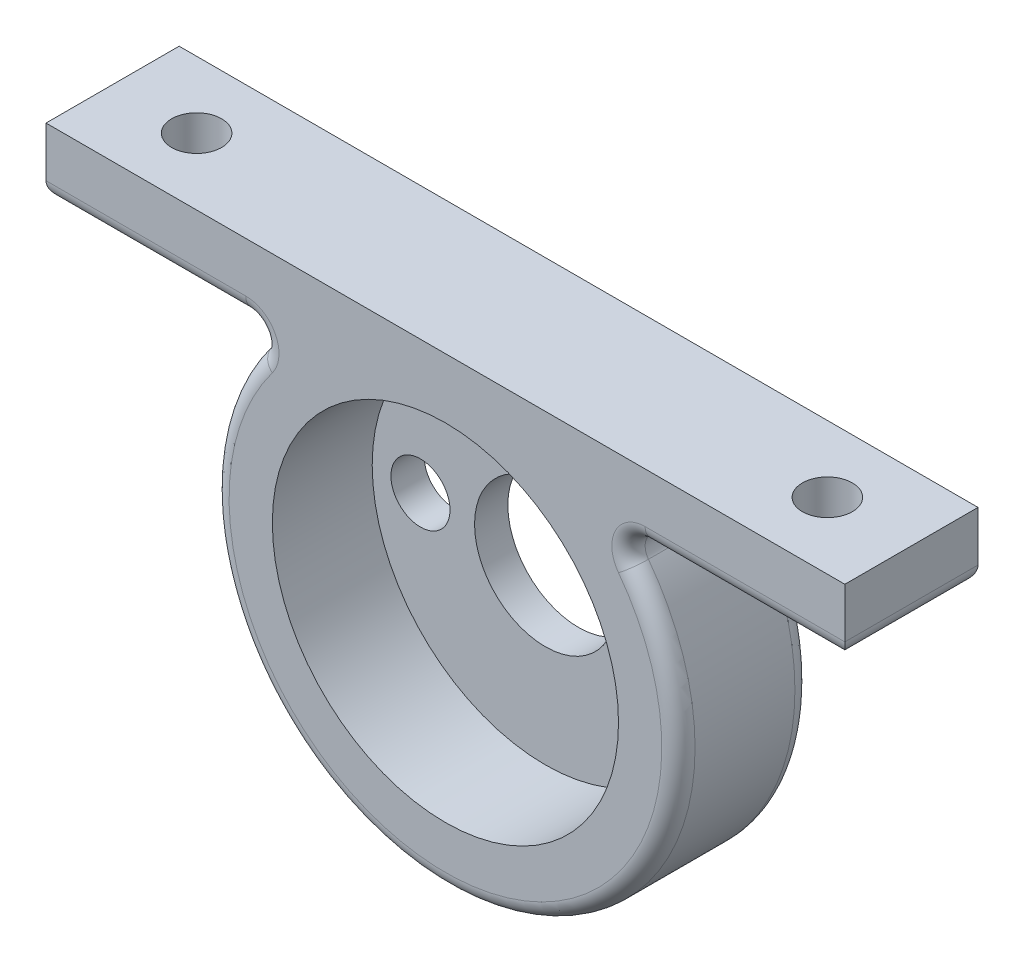
SolidWorks part; units mm, degrees
ref_plane "Alzado" through (0, 0, 0) normal (0, 0, 1) x (1, 0, 0)
ref_plane "Planta" through (0, 0, 0) normal (0, 1, 0) x (1, 0, 0)
ref_plane "Vista lateral" through (0, 0, 0) normal (1, 0, 0) x (0, 0, -1)
sketch "Croquis1" plane through (0, 0, 0) normal (0, 0, 1) x (1, 0, 0)
  line L0 (0, 14) -> (24, 14)
  line L1 (0, 14) -> (-24, 14)
  line L2 (-24, 14) -> (-24, 10)
  line L3 (-24, 10) -> (-9.798, 10)
  line L4 (24, 14) -> (24, 10)
  line L5 (24, 10) -> (9.798, 10)
  arc A1 (-9.798, 10) -> (9.798, 10) centre (0, 0) ccw
  dimension "D1" = 14
  dimension "D2" = 14
  dimension "D3" = 48
  dimension "D5" = 4
  dimension "D6" = 4
  dimension "D7" = 24
extrude "Saliente-Extruir1" add sketch "Croquis1" along normal blind 8
fillet "Redondeo1" radius 1 10 edges at (-16.899, 10, 8) (-16.899, 10, 0) (16.899, 10, 8) (16.899, 10, 0) (-9.798, 10, 4) (0, -14, 8) (9.798, 10, 4) (0, -14, 0) (24, 10, 4) (-24, 10, 4)
sketch "Croquis2" plane through (0, 10, 0) normal (0, -1, 0) x (1, 0, 0)
  line L0 (23, 1) -> (23, 7) construction
  line L2 (12, 1) -> (23, 1) construction
  line L4 (-23, 1) -> (-12, 1) construction
  line L5 (-23, 7) -> (-23, 1) construction
  circle A0 centre (-18.9495, 4) radius 1.5
  circle A1 centre (18.9495, 4) radius 1.5
  dimension "D1" = 3
  dimension "D2" = 3
  dimension "D3" = 4.0505
  dimension "D4" = 3
  dimension "D5" = 3
  dimension "D6" = 4.0505
extrude "Cortar-Extruir1" cut sketch "Croquis2" against normal through all
sketch "Croquis3" plane through (0, 0, 8) normal (0, 0, 1) x (1, 0, 0)
  circle A0 centre (0, 0) radius 10.4
  dimension "D1" = 20.8
extrude "Cortar-Extruir2" cut sketch "Croquis3" against normal blind 6
sketch "Croquis4" plane through (0, 0, 0) normal (0, 0, -1) x (-1, 0, 0)
  line L0 (-24, 14) -> (24, 14) construction
  circle A0 centre (0, 0) radius 4.25
  circle A1 centre (7.5, 0) radius 1.775
  circle A2 centre (-7.5, 0) radius 1.775
  dimension "D1" = 8.5
  dimension "D2" = 7.5
  dimension "D3" = 7.5
  dimension "D4" = 3.55
  dimension "D5" = 3.55
  dimension "D6" = 14
  dimension "D7" = 14
extrude "Cortar-Extruir3" cut sketch "Croquis4" against normal through all
